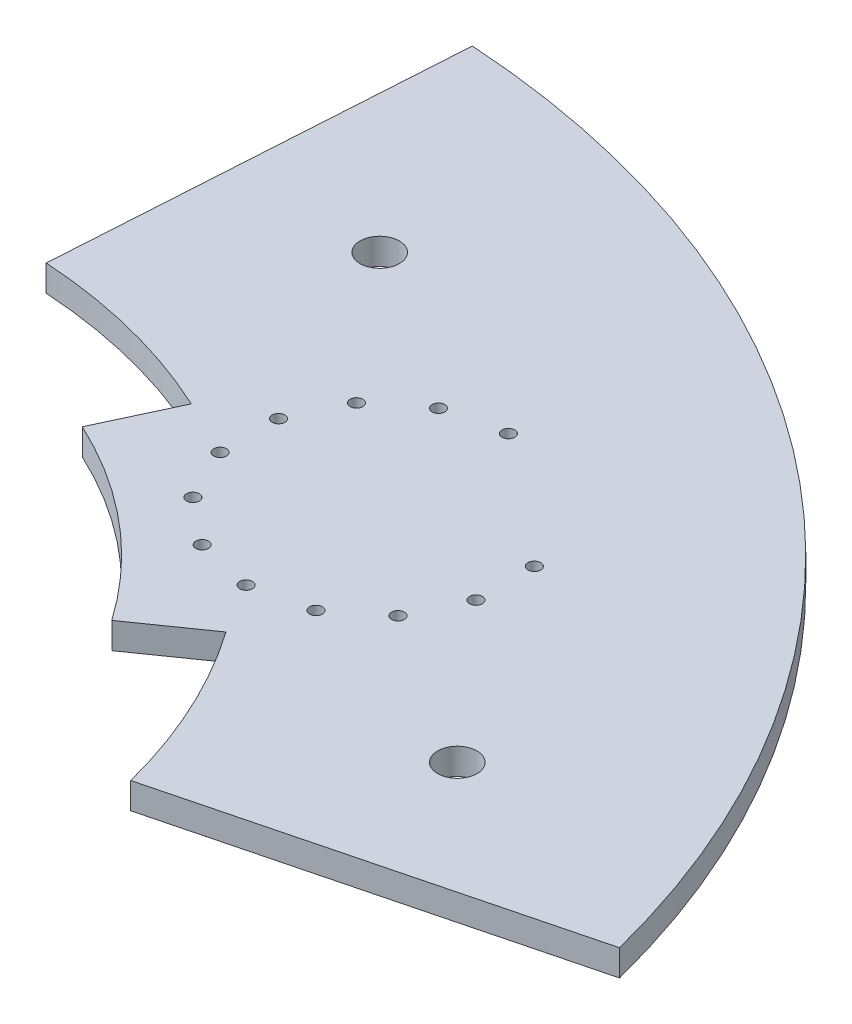
SolidWorks part; units mm, degrees
ref_plane "Front Plane" through (0, 0, 0) normal (0, 0, 1) x (1, 0, 0)
ref_plane "Top Plane" through (0, 0, 0) normal (0, 1, 0) x (1, 0, 0)
ref_plane "Right Plane" through (0, 0, 0) normal (1, 0, 0) x (0, 0, -1)
sketch "Sketch2" plane through (0, 0, 0) normal (0, 1, 0) x (1, 0, 0)
  line L0 (-13.9738, -4.5131) -> (-12.8493, 13.4297)
  line L1 (-109.1141, 86.0334) -> (-70.8259, 95.8313) construction
  line L2 (21.8423, -34.1597) -> (39.2591, -29.7028)
  line L3 (-106.642, 125.478) -> (-109.1141, 86.0334) construction
  line L4 (-16.4459, -43.9577) -> (7.7371, -27.0246) construction
  line L5 (-16.4459, -43.9577) -> (-3.9899, -17.1921) construction
  line L6 (-109.1141, 86.0334) -> (-83.9464, 116.0505) construction
  line L7 (-13.9738, -4.5131) -> (-14.3818, -11.0224)
  line L8 (21.8423, -34.1597) -> (15.5239, -35.7766)
  line L9 (-3.9899, -17.1921) -> (-2.5225, -14.0389)
  line L10 (-16.4459, -43.9577) -> (21.8423, -34.1597) construction
  line L11 (7.7371, -27.0246) -> (10.5861, -25.0297)
  line L12 (-13.9738, -4.5131) -> (-16.4459, -43.9577) construction
  line L13 (-16.4459, -43.9577) -> (8.7219, -13.9406) construction
  line L14 (-4.6321, -18.572) -> (-3.9899, -17.1921)
  line L15 (7.7371, -27.0246) -> (6.4904, -27.8976)
  circle A0 centre (8.7219, -13.9406) radius 5
  arc A1 (-14.6001, -14.4935) -> (-14.5993, -14.4935) centre (-16.4459, -43.9577) cw
  arc A2 (-2.5225, -14.0389) -> (-14.3818, -11.0224) centre (-16.4459, -43.9577) ccw
  circle A3 centre (-83.9464, 116.0505) radius 6
  arc A6 (-107.2684, 115.4976) -> (-80.5137, 93.3521) centre (-109.1141, 86.0334) cw
  arc A7 (-106.642, 125.478) -> (-70.8259, 95.8313) centre (-109.1141, 86.0334) cw
  arc A9 (6.4904, -27.8976) -> (-4.6321, -18.572) centre (-16.4459, -43.9577) ccw
  arc A10 (15.5239, -35.7766) -> (10.5861, -25.0297) centre (-16.4459, -43.9577) ccw
  arc A11 (39.2591, -29.7028) -> (-12.8493, 13.4297) centre (-16.4459, -43.9577) ccw
extrude "Boss-Extrude1" add sketch "Sketch2" along normal blind 1.6
sketch "Sketch3" plane through (0, 1.6, 0) normal (0, 1, 0) x (1, 0, 0)
  line L0 (-16.4459, -43.9577) -> (23.4317, -25.3625) construction
  line L1 (-16.4459, -43.9577) -> (8.7219, -13.9406) construction
  line L2 (-16.4459, -43.9577) -> (-5.0905, -1.4483) construction
  circle A2 centre (-4.7808, -0.2889) radius 1.2
  circle A3 centre (24.5192, -24.8554) radius 1.2
  dimension "D1" = 2.4
  dimension "D2" = 2.4
extrude "Cut-Extrude1" cut sketch "Sketch3" against normal blind 1.7
sketch "Sketch5" plane through (0, 0, 0) normal (0, 1, 0) x (-0.1997, 0, 0.9799)
  line L2 (31.9563, 22.3551) -> (21.2654, 44.3995) construction
  line L3 (26.6109, 33.3773) -> (15.623, 25.5333) construction
  line L4 (-10.5935, -15.2721) -> (13.6721, -11.8912) construction
  line L5 (1.5393, -13.5817) -> (2.0394, 0.4732) construction
  circle A1 centre (15.623, 25.5333) radius 4.8936
  circle A2 centre (2.0394, 0.4732) radius 4.8936
  dimension "D2" = 80.35
  dimension "D3" = 80.03
sketch "Sketch10" plane through (0, 1.6, 0) normal (0, 1, 0) x (1, 0, 0)
  line L0 (8.7219, -13.9406) -> (8.7219, -5.9406) construction
  circle A0 centre (5.2508, -6.7328) radius 0.39
  circle A1 centre (8.7219, -5.9406) radius 0.39
  circle A2 centre (2.4672, -8.9527) radius 0.39
  circle A3 centre (0.9224, -12.1604) radius 0.39
  circle A4 centre (0.9224, -15.7207) radius 0.39
  circle A5 centre (2.4672, -18.9285) radius 0.39
  circle A6 centre (5.2508, -21.1483) radius 0.39
  circle A7 centre (8.7219, -21.9406) radius 0.39
  circle A8 centre (12.1929, -21.1483) radius 0.39
  circle A9 centre (14.9765, -18.9285) radius 0.39
  circle A10 centre (16.5213, -15.7207) radius 0.39
  circle A11 centre (16.5213, -12.1604) radius 0.39
  circle A14 centre (12.1929, -6.7328) radius 0.39 [skipped]
  circle A15 centre (14.9765, -8.9527) radius 0.39 [skipped]
  dimension "D1" = 0.78
  dimension "D2" = 14
extrude "Cut-Extrude6" cut sketch "Sketch10" against normal blind 10
sketch "Sketch11" plane through (0, 1.6, 0) normal (0, 1, 0) x (1, 0, 0)
  circle A0 centre (8.7219, -13.9406) radius 5
extrude "Boss-Extrude3" add sketch "Sketch11" against normal blind 1.7
sketch "Sketch13" plane through (0, 1.6, 0) normal (0, 1, 0) x (1, 0, 0)
  line L0 (-4.6321, -18.572) -> (-2.5225, -14.0389)
  line L1 (-2.5225, -14.0389) -> (-0.4128, -9.5057)
  line L2 (6.4904, -27.8976) -> (10.5861, -25.0297)
  line L3 (10.5861, -25.0297) -> (14.6819, -22.1618)
  arc A0 (-0.4128, -9.5057) -> (14.6819, -22.1618) centre (-16.4459, -43.9577) cw
  dimension "D2" = 38
  dimension "D1" = 10
